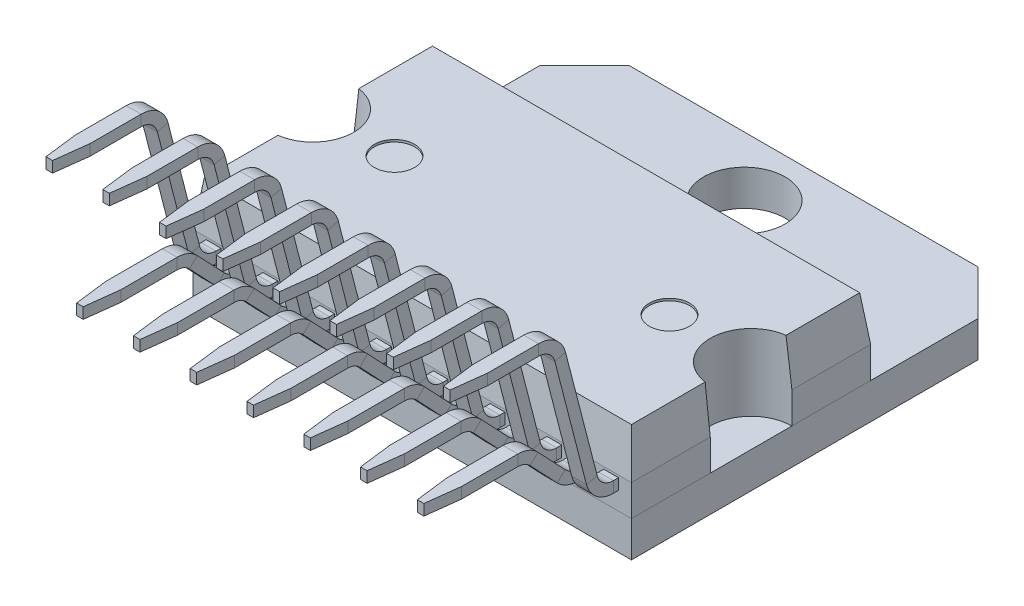
SolidWorks part; units mm, degrees
ref_plane "前视基准面" through (0, 0, 0) normal (0, 0, 1) x (1, 0, 0)
ref_plane "上视基准面" through (0, 0, 0) normal (0, 1, 0) x (1, 0, 0)
ref_plane "右视基准面" through (0, 0, 0) normal (1, 0, 0) x (0, 0, -1)
sketch "草图1" plane through (0, 0, 0) normal (0, 1, 0) x (1, 0, 0)
  line L0 (0, 0) -> (-9.8, 0)
  line L1 (-9.8, 0) -> (-9.8, 15.5)
  line L2 (-7.8, 17.5) -> (7.8, 17.5)
  line L3 (9.8, 15.5) -> (9.8, 0)
  line L4 (9.8, 0) -> (0, 0)
  line L5 (-9.8, 15.5) -> (-7.8, 17.5)
  line L6 (7.8, 17.5) -> (9.8, 15.5)
  circle A0 centre (0, 14.85) radius 1.825
  point P3 (-9.8, 17.5)
  point P4 (9.8, 17.5)
  point P12 (0, 0)
  dimension "D4" = 3.65
  dimension "D1" = 17.5
  dimension "D2" = 19.6
  dimension "D3" = 2.65
extrude "凸台-拉伸1" add sketch "草图1" along normal blind 1.6
sketch "草图2" plane through (0, 1.6, 0) normal (0, 1, 0) x (1, 0, 0)
  line L0 (9.8, 0) -> (9.8, 15.5) construction
  line L1 (-9.8, 0) -> (9.8, 0)
  line L2 (-9.8, 0) -> (-9.8, 10.7)
  line L3 (-9.8, 10.7) -> (9.8, 10.7)
  line L4 (9.8, 0) -> (9.8, 10.7)
  dimension "D1" = 10.7
extrude "凸台-拉伸2" add sketch "草图2" along normal blind 3.4 separate body
chamfer "倒角1" distance 2 angle 7 4 edges at (0, 5, -10.7) (9.8, 5, -5.35) (0, 5, 0) (-9.8, 5, -5.35)
sketch "草图3" plane through (0, 5, 0) normal (0, 1, 0) x (1, 0, 0)
  line L0 (-9.8, 5.35) -> (9.8, 5.35) construction
  line L1 (-9.8, 0) -> (-9.8, 10.7) construction
  line L2 (9.8, 10.7) -> (9.8, 0) construction
  circle A0 centre (-9.8, 5.35) radius 1.825
  circle A1 centre (9.8, 5.35) radius 1.825
  dimension "D1" = 3.65
  dimension "D2" = 3.65
extrude "切除-拉伸1" cut sketch "草图3" against normal blind 3.4
sketch "草图4" plane through (0, 5, 0) normal (0, 1, 0) x (1, 0, 0)
  line L0 (0, 10.7) -> (0, 0) construction
  line L1 (-9.8, 15.5) -> (-9.8, 0) construction
  line L2 (-9.8, 10.7) -> (9.8, 10.7) construction
  circle A0 centre (-6.15, 5.35) radius 0.9
  circle A1 centre (6.15, 5.35) radius 0.9
  point P7 (0, 0)
  point P11 (0, 5.35)
  dimension "D1" = 1.8
  dimension "D2" = 3.65
extrude "切除-拉伸2" cut sketch "草图4" against normal blind 0.1
sketch "草图5" plane through (0, 0, 0) normal (1, 0, 0) x (0, 0, -1)
  line L0 (0, 0) -> (0, 5) construction
  line L1 (0.2456, 5) -> (3.5416, 5) construction
  line L2 (0, 2.65) -> (-0.5699, 2.65)
  line L3 (0, 0) -> (15.5, 0) construction
  line L4 (-3.2301, 4.55) -> (-7.25, 4.55)
  line L5 (-2.5042, 4.2377) -> (-1.2958, 2.9623)
  arc A0 (-0.5699, 2.65) -> (-1.2958, 2.9623) centre (-0.5699, 3.65) cw
  arc A1 (-2.5042, 4.2377) -> (-3.2301, 4.55) centre (-3.2301, 3.55) ccw
  point P6 (0, 2.65)
  point P8 (14.85, 0)
  point P9 (-2.8, 4.55)
  point P13 (-2.8, 0)
  point P14 (-7.25, 0)
  point P19 (-1, 2.65)
  point P22 (-2.8, 4.55)
  dimension "D6" = 1
  dimension "D1" = 2.65
  dimension "D2" = 1
  dimension "D3" = 2.65
  dimension "D4" = 17.65
  dimension "D5" = 4.55
  dimension "D7" = 22.1
sketch "草图6" plane through (0, 0, 0) normal (0, 0, 1) x (1, 0, 0)
  line L5 (-0.33, 2.405) -> (0.33, 2.895) construction
  line L6 (-0.33, 2.895) -> (0.33, 2.405) construction
  line L115 (-0.33, 2.405) -> (0.33, 2.405)
  line L116 (-0.33, 2.405) -> (-0.33, 2.895)
  line L117 (-0.33, 2.895) -> (0.33, 2.895)
  line L118 (0.33, 2.405) -> (0.33, 2.895)
  line L119 (-0.33, 2.405) -> (0.33, 2.895) construction
  line L120 (-0.33, 2.895) -> (0.33, 2.405) construction
  point P0 (0, 2.65)
  point P6 (0, 2.65)
  dimension "D1" = 0.66
  dimension "D2" = 0.49
sketch "草图7" plane through (0, 0, 0) normal (1, 0, 0) x (0, 0, -1)
  line L0 (0, 0) -> (0, 5) construction
  line L2 (0, 2.65) -> (-0.2252, 2.65)
  line L3 (0, 0) -> (15.5, 0) construction
  line L4 (-3.5748, 9.63) -> (-7.35, 9.63)
  line L5 (-2.6065, 8.8797) -> (-1.1935, 3.4003)
  line L6 (0.2456, 5) -> (3.5416, 5) construction
  arc A0 (-0.2252, 2.65) -> (-1.1935, 3.4003) centre (-0.2252, 3.65) cw
  arc A1 (-2.6065, 8.8797) -> (-3.5748, 9.63) centre (-3.5748, 8.63) ccw
  point P2 (0, 0)
  point P4 (0, 0)
  point P5 (0, 0)
  point P6 (0, 2.65)
  point P8 (14.85, 0)
  point P9 (-2.8, 9.63)
  point P12 (0, 0)
  point P13 (-2.8, 0)
  point P14 (-7.35, 0)
  point P19 (-1, 2.65)
  point P22 (-2.8, 9.63)
  point P24 (0, 0)
  dimension "D6" = 1
  dimension "D1" = 2.65
  dimension "D2" = 1
  dimension "D4" = 17.65
  dimension "D5" = 9.63
  dimension "D7" = 22.2
  dimension "D3" = 2.65
sweep "扫描2" add profiles "草图6" path "草图5"
chamfer "倒角2" distance 1.5 angle 7 2 edges at (-0.33, 4.55, 7.25) (0.33, 4.55, 7.25)
pattern_linear "阵列(线性)4" count 4 spacing 2.54 along (1, 0, 0) count 4 spacing 2.54 along (-1, 0, 0) of "扫描2", "倒角2"
sketch "草图8" plane through (0, 0, 0) normal (0, 0, 1) x (1, 0, 0)
  line L1 (8.56, 2.405) -> (9.22, 2.405)
  line L2 (8.56, 2.405) -> (8.56, 2.895)
  line L3 (8.56, 2.895) -> (9.22, 2.895)
  line L4 (9.22, 2.405) -> (9.22, 2.895)
  line L5 (8.56, 2.405) -> (9.22, 2.895) construction
  line L6 (8.56, 2.895) -> (9.22, 2.405) construction
  point P0 (8.89, 2.65)
  point P5 (0, 0)
  dimension "D1" = 0.66
  dimension "D2" = 0.49
  dimension "D3" = 8.89
sweep "扫描3" add profiles "草图8" path "草图7"
chamfer "倒角3" distance 1.5 angle 7 2 edges at (8.56, 9.63, 7.35) (9.22, 9.63, 7.35)
pattern_linear "阵列(线性)5" count 8 spacing 2.54 along (-1, 0, 0) of "扫描3", "倒角3"
sketch "草图9" plane through (0, 1.6, 0) normal (0, 1, 0) x (1, 0, 0)
  line L1 (1.6, -3.5748) -> (0.94, -3.5748) construction
  point P0 (0, 14.85)
  dimension "D1" = 18.4248
equation "\"D3@草图8\"=1.27*7"
equation "\"D5@草图7\"=4.55+5.08"
